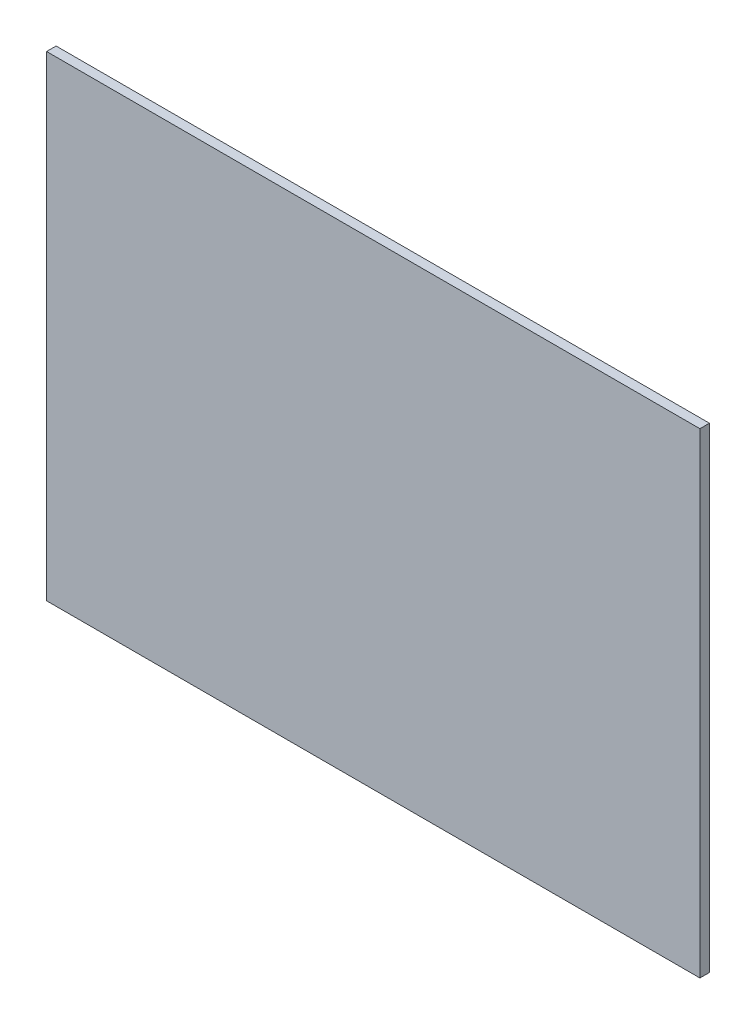
SolidWorks part; units mm, degrees
ref_plane "Front Plane" through (0, 0, 0) normal (0, 0, 1) x (1, 0, 0)
ref_plane "Top Plane" through (0, 0, 0) normal (0, 1, 0) x (1, 0, 0)
ref_plane "Right Plane" through (0, 0, 0) normal (1, 0, 0) x (0, 0, -1)
sketch "Sketch1" plane through (0, 0, 0) normal (0, 0, 1) x (1, 0, 0)
  line L1 (-103, -75) -> (103, -75)
  line L2 (-103, -75) -> (-103, 75)
  line L3 (-103, 75) -> (103, 75)
  line L4 (103, -75) -> (103, 75)
  line L5 (-103, -75) -> (103, 75) construction
  line L6 (-103, 75) -> (103, -75) construction
  point P0 (0, 0)
  dimension "D1" = 206
  dimension "D2" = 150
extrude "Boss-Extrude1" add sketch "Sketch1" along normal blind 3
